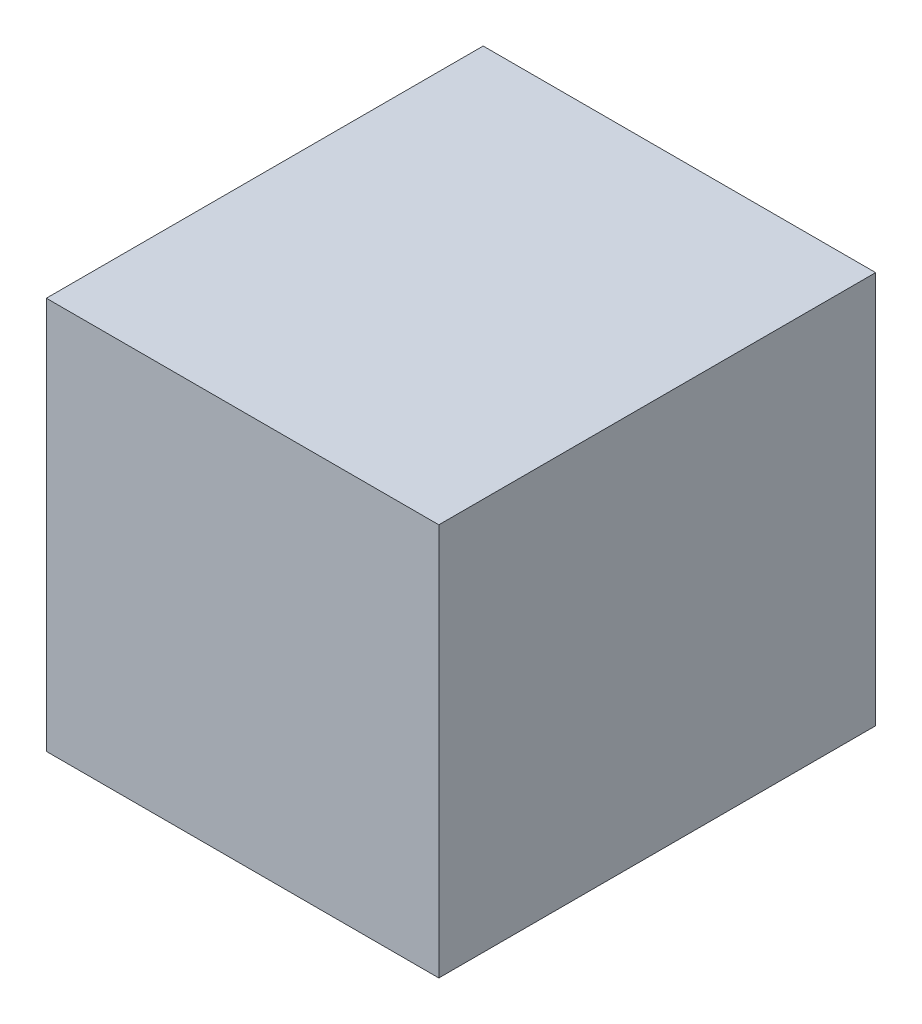
SolidWorks part; units mm, degrees
ref_plane "Front Plane" through (0, 0, 0) normal (0, 0, 1) x (1, 0, 0)
ref_plane "Top Plane" through (0, 0, 0) normal (0, 1, 0) x (1, 0, 0)
ref_plane "Right Plane" through (0, 0, 0) normal (1, 0, 0) x (0, 0, -1)
sketch "Sketch1" plane through (0, 0, 0) normal (0, 0, 1) x (1, 0, 0)
  line L1 (-44.958, -44.958) -> (44.958, -44.958)
  line L2 (-44.958, -44.958) -> (-44.958, 44.958)
  line L3 (-44.958, 44.958) -> (44.958, 44.958)
  line L4 (44.958, -44.958) -> (44.958, 44.958)
  line L5 (-44.958, -44.958) -> (44.958, 44.958) construction
  line L6 (-44.958, 44.958) -> (44.958, -44.958) construction
  point P0 (0, 0)
  dimension "D1" = 89.916
extrude "Boss-Extrude1" add sketch "Sketch1" along normal blind 100.076
